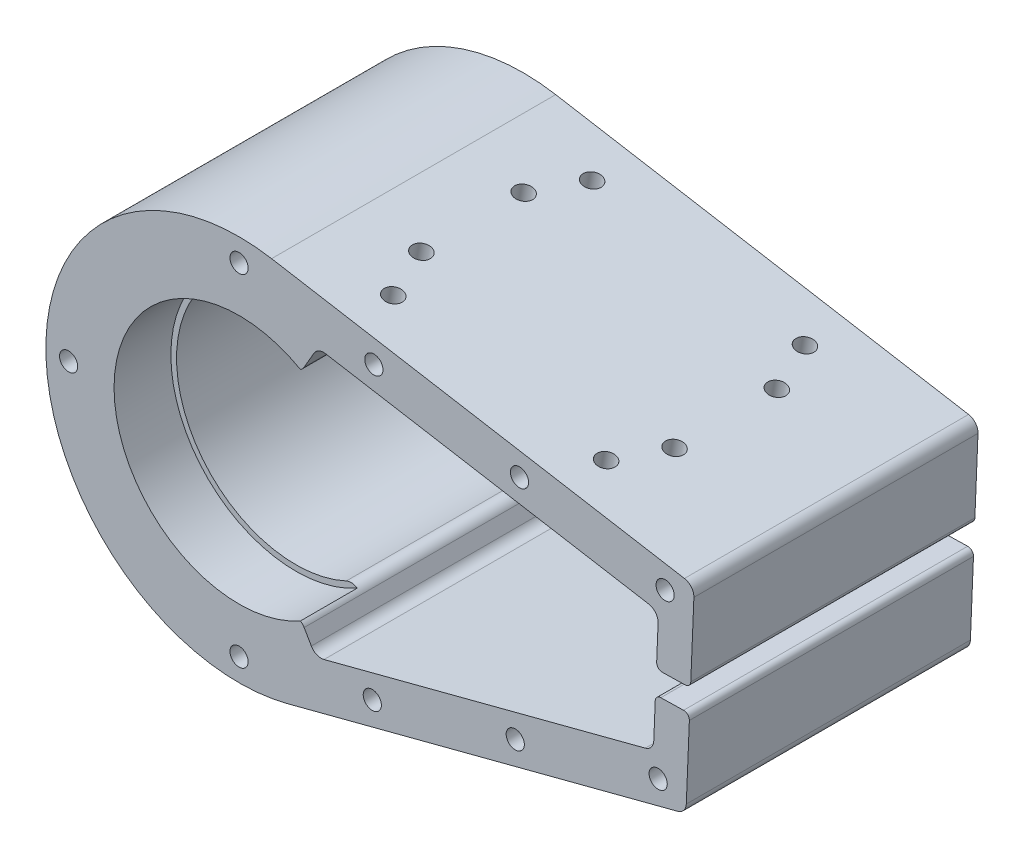
SolidWorks part; units mm, degrees
material "ABS"
ref_plane "前视基准面" through (0, 0, 0) normal (0, 0, 1) x (1, 0, 0)
ref_plane "上视基准面" through (0, 0, 0) normal (0, 1, 0) x (1, 0, 0)
ref_plane "右视基准面" through (0, 0, 0) normal (1, 0, 0) x (0, 0, -1)
sketch "草图1" plane through (0, 0, 0) normal (0, 0, 1) x (1, 0, 0)
  line L0 (0, 0) -> (-95, 0) construction
  line L1 (-86.4105, 32.8971) -> (2.5263, 9.6756)
  line L2 (-86.4105, -32.8971) -> (2.5263, -9.6756)
  arc A0 (-86.4105, 32.8971) -> (-86.4105, -32.8971) centre (-95, 0) ccw
  arc A1 (2.5263, -9.6756) -> (2.5263, 9.6756) centre (0, 0) ccw
  dimension "D2" = 68
  dimension "D3" = 20
  dimension "D1" = 95
extrude "凸台-拉伸1" add sketch "草图1" along normal blind 50
sketch "草图2" plane through (0, 0, 50) normal (0, 0, 1) x (1, 0, 0)
  circle A0 centre (-95, 0) radius 26
  dimension "D1" = 52
extrude "切除-拉伸1" cut sketch "草图2" against normal blind 50
sketch "草图4" plane through (0, 0, 50) normal (0, 0, 1) x (1, 0, 0)
  line L1 (-89.2737, 33.5143) -> (0, 18.2609)
  line L2 (0, 18.2609) -> (0, 0)
  line L3 (-89.2737, 33.5143) -> (0, 0)
  arc A0 (-86.4105, 32.8971) -> (-86.4105, -32.8971) centre (-95, 0) ccw construction
  dimension "D1" = 18.2609
  dimension "D2" = 90.5674
extrude "凸台-拉伸2" add sketch "草图4" against normal up to surface (50 mm away) up to face at (-69, 0, 0)
sketch "草图3" plane through (0, 0, 50) normal (0, 0, 1) x (1, 0, 0)
  line L2 (-67.2333, -19.6217) -> (-22.0766, -7.8313)
  line L3 (-21.1786, 13.7635) -> (-69.0251, 21.9387)
  line L5 (-21.1786, 13.7635) -> (-22.0766, -7.8313)
  line L8 (-71.5518, -24.8834) -> (-21.2385, -11.7465) construction
  line L9 (-21.2385, -11.7465) -> (0, 0) construction
  line L10 (-71.2744, 26.381) -> (-45.6458, 22.002) construction
  line L11 (-45.6458, 22.002) -> (-20.0172, 17.6231) construction
  line L12 (-20.0172, 17.6231) -> (0, 0) construction
  line L14 (-95, 30) -> (-95, 0) construction
  line L15 (-95, 0) -> (-125, 0) construction
  line L16 (-95, 0) -> (-95, -30) construction
  line L17 (-86.4105, -32.8971) -> (2.5263, -9.6756) construction
  line L18 (0, 18.2609) -> (-89.2737, 33.5143) construction
  line L19 (-14.8807, 20.8034) -> (-16.353, -14.605) construction
  circle A8 centre (-95, 30) radius 1.6
  circle A9 centre (-125, 0) radius 1.6
  circle A10 centre (-95, -30) radius 1.6
  circle A11 centre (-71.5518, -24.8834) radius 1.6
  circle A12 centre (-71.2744, 26.381) radius 1.6
  circle A13 centre (-45.6458, 22.002) radius 1.6
  circle A14 centre (-21.2385, -11.7465) radius 1.6
  circle A15 centre (-20.0172, 17.6231) radius 1.6
  circle A16 centre (-95, 0) radius 30 construction
  circle A19 centre (-46.3951, -18.315) radius 1.6
  arc A20 (-67.2333, -19.6217) -> (-69.0251, 21.9387) centre (-95, 0) ccw
  dimension "D3" = 34
  dimension "D4" = 60
  dimension "D5" = 3.2
  dimension "D6" = 3.2
  dimension "D2" = 5
  dimension "D7" = 17.6231
  dimension "D8" = 20.0172
  dimension "D9" = 26
  dimension "D10" = 26
  dimension "D11" = 52
  dimension "D12" = 11.7465
  dimension "D13" = 24.2705
  dimension "D14" = 8
  dimension "D15" = 8
  dimension "D16" = 5
  dimension "D17" = 6
extrude "切除-拉伸2" cut sketch "草图3" against normal blind 68
sketch "草图5" plane through (0, 0, 50) normal (0, 0, 1) x (1, 0, 0)
  line L1 (0, 18.2609) -> (-89.2737, 33.5143) construction
  line L2 (-16.0817, -8.0805) -> (-15.1838, 13.5143)
  line L3 (-16.353, -14.605) -> (-14.8807, 20.8034)
  line L4 (-86.4105, -32.8971) -> (2.5263, -9.6756) construction
  dimension "D1" = 6
extrude "切除-拉伸-薄壁1" cut sketch "草图5" against normal blind 58 and the other way through all thin
sketch "草图6" plane through (0, 0, 50) normal (0, 0, 1) x (1, 0, 0)
  line L0 (-90.6211, 25.6286) -> (-69.0251, 21.9387)
  line L1 (-88.4316, -25.1566) -> (-67.2333, -19.6217)
  circle A0 centre (-95, 0) radius 26 construction
  arc A1 (-88.4316, -25.1566) -> (-90.6211, 25.6286) centre (-95, 0) ccw
  arc A2 (-67.2333, -19.6217) -> (-69.0251, 21.9387) centre (-95, 0) ccw construction
  arc A3 (-67.2333, -19.6217) -> (-69.0251, 21.9387) centre (-95, 0) ccw
extrude "切除-拉伸3" cut sketch "草图6" against normal blind 58
sketch "草图7" plane through (0, 0, 50) normal (0, 0, 1) x (1, 0, 0)
  line L0 (-82, 22.5167) -> (-84.5, 18.1865)
  line L1 (-84.5, -18.1865) -> (-82, -22.5167)
  line L2 (-95, 0) -> (-84.5, -18.1865) construction
  line L3 (-95, 0) -> (-84.5, 18.1865) construction
  line L4 (-95, 0) -> (0, 0) construction
  arc A0 (-84.5, 18.1865) -> (-84.5, -18.1865) centre (-95, 0) ccw
  arc A1 (-90.6211, 25.6286) -> (-88.4316, -25.1566) centre (-95, 0) ccw construction
  arc A2 (-82, 22.5167) -> (-82, -22.5167) centre (-95, 0) ccw
  dimension "D1" = 42
  dimension "D2" = 120
  dimension "D3" = 60
extrude "凸台-拉伸3" add sketch "草图7" against normal up to surface (50 mm away) up to face at (-18.4172, 17.6231, 0)
fillet "圆角1" radius 2 6 edges at (-16.353, -14.605, 25) (-14.8807, 20.8034, 25) (-22.0766, -7.8313, 25) (-21.1786, 13.7635, 25) (-84.5, -18.1865, 25) (-84.5, 18.1865, 25)
sketch "草图8" plane through (0, 0, 50) normal (0, 0, 1) x (1, 0, 0)
  circle A0 centre (-95, 0) radius 22
  arc A1 (-86.1212, 19.0307) -> (-86.1212, -19.0307) centre (-95, 0) ccw construction
  dimension "D1" = 1
extrude "切除-拉伸4" cut sketch "草图8" against normal blind 10
sketch "草图9" plane through (0, 0, 0) normal (0, 0, -1) x (-1, 0, 0)
  circle A0 centre (95, 0) radius 23.5
  arc A1 (86.1212, -19.0307) -> (86.1212, 19.0307) centre (95, 0) ccw construction
  dimension "D1" = 2.5
extrude "切除-拉伸5" cut sketch "草图9" against normal blind 6
sketch "草图10" plane through (0, 0, 50) normal (0, 0, 1) x (1, 0, 0)
  line L0 (-90.6211, 25.6286) -> (-81.1387, 24.0084)
  line L1 (-22.9131, 14.0599) -> (-90.6211, 25.6286) construction
  line L2 (-81.1387, 24.0084) -> (-82, 22.5167)
  line L3 (-83.5436, 19.8431) -> (-82, 22.5167) construction
  line L4 (-82, -22.5167) -> (-81.518, -23.3515)
  line L5 (-88.4316, -25.1566) -> (-23.5081, -8.205) construction
  line L6 (-82, -22.5167) -> (-83.5436, -19.8431) construction
  line L7 (-88.4316, -25.1566) -> (-81.518, -23.3515)
  arc A0 (-82, 22.5167) -> (-90.6211, 25.6286) centre (-95, 0) ccw construction
  arc A1 (-82, 22.5167) -> (-90.6211, 25.6286) centre (-95, 0) ccw
  arc A2 (-88.4316, -25.1566) -> (-82, -22.5167) centre (-95, 0) ccw construction
  arc A3 (-88.4316, -25.1566) -> (-82, -22.5167) centre (-95, 0) ccw
extrude "凸台-拉伸4" add sketch "草图10" against normal up to surface (50 mm away) up to face at (-18.4172, 17.6231, 0)
fillet "圆角2" radius 2 2 edges at (-81.1387, 24.0084, 25) (-81.518, -23.3515, 25)
sketch "草图11" plane through (3.0316, 17.7429, 0) normal (0.1684, 0.9857, 0) x (0.9857, -0.1684, 0)
  line L0 (-60.5315, -25) -> (-19.9315, -25) construction
  line L1 (-83.1315, -34) -> (-37.9315, -34) construction
  line L2 (-83.1315, -34) -> (-83.1315, -16) construction
  line L3 (-83.1315, -16) -> (-37.9315, -16) construction
  line L4 (-37.9315, -34) -> (-37.9315, -16) construction
  line L5 (-60.5315, -16) -> (-60.5315, -34) construction
  line L6 (-83.1315, -25) -> (-37.9315, -25) construction
  line L7 (-19.9315, -50) -> (-19.9315, 0) construction
  circle A0 centre (-37.9315, -16) radius 1.6
  circle A1 centre (-83.1315, -16) radius 1.6
  circle A2 centre (-83.1315, -34) radius 1.6
  circle A3 centre (-37.9315, -34) radius 1.6
  dimension "D4" = 3.2
  dimension "D1" = 18
  dimension "D2" = 45.2
  dimension "D3" = 18
extrude "切除-拉伸6" cut sketch "草图11" against normal blind 24
sketch "草图12" plane through (3.0316, 17.7429, 0) normal (0.1684, 0.9857, 0) x (0.9857, -0.1684, 0)
  line L0 (-83.1315, -16) -> (-37.9315, -34) construction
  line L2 (-79.5315, -42.5) -> (-41.5315, -42.5) construction
  line L3 (-79.5315, -42.5) -> (-79.5315, -7.5) construction
  line L4 (-79.5315, -7.5) -> (-41.5315, -7.5) construction
  line L5 (-41.5315, -42.5) -> (-41.5315, -7.5) construction
  line L6 (-79.5315, -42.5) -> (-41.5315, -7.5) construction
  line L7 (-79.5315, -7.5) -> (-41.5315, -42.5) construction
  circle A0 centre (-79.5315, -7.5) radius 1.6
  circle A1 centre (-41.5315, -7.5) radius 1.6
  circle A2 centre (-79.5315, -42.5) radius 1.6
  circle A3 centre (-41.5315, -42.5) radius 1.6
  circle A4 centre (-37.9315, -16) radius 1.6 construction
  point P4 (-60.5315, -25)
  dimension "D1" = 38
  dimension "D2" = 35
extrude "切除-拉伸7" cut sketch "草图12" against normal blind 10
sketch "草图13" plane through (0, 0, 50) normal (0, 0, 1) x (1, 0, 0)
  line L0 (-21.5501, 4.8285) -> (-15.5394, 4.9616)
  line L1 (-22.0151, -6.353) -> (-21.2517, 12.0054) construction
  line L2 (-14.9538, 19.0452) -> (-16.2916, -13.1268) construction
  line L3 (-21.7167, 0.8239) -> (-15.7059, 0.9569)
  line L4 (-21.6334, 2.8262) -> (-15.6227, 2.9592) construction
  line L5 (-21.5501, 4.8285) -> (-21.7167, 0.8239)
  line L6 (-15.5394, 4.9616) -> (-15.7059, 0.9569)
  dimension "D1" = 4
extrude "切除-拉伸8" cut sketch "草图13" against normal blind 72
fillet "圆角3" radius 1 4 edges at (-21.7167, 0.8239, 25) (-15.7059, 0.9569, 25) (-15.5394, 4.9616, 25) (-21.5501, 4.8285, 25)
